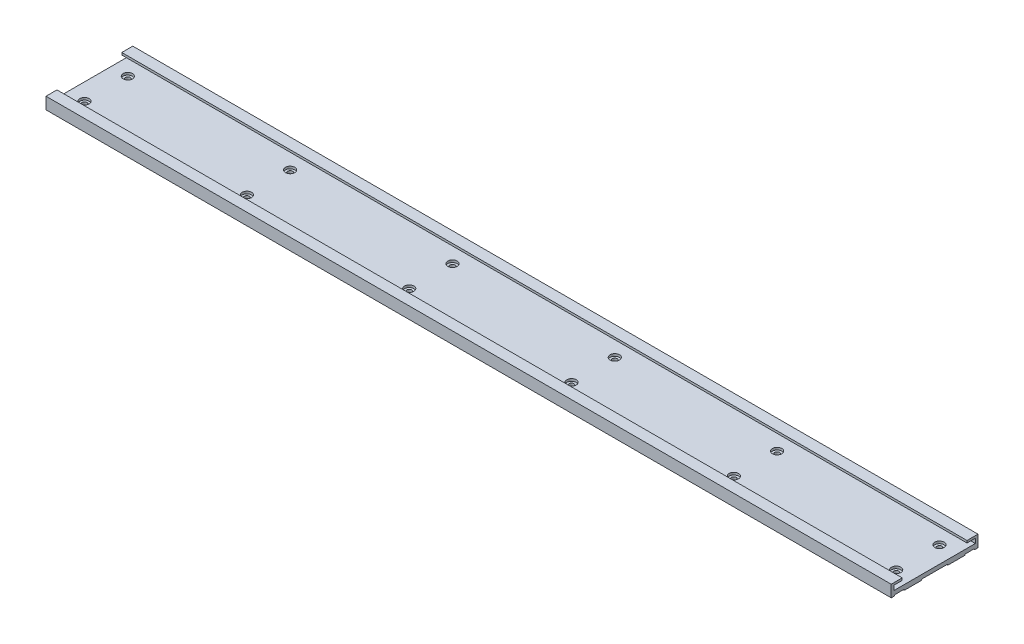
SolidWorks part; units mm, degrees
ref_plane "Front Plane" through (0, 0, 0) normal (0, 0, 1) x (1, 0, 0)
ref_plane "Top Plane" through (0, 0, 0) normal (0, 1, 0) x (1, 0, 0)
ref_plane "Right Plane" through (0, 0, 0) normal (1, 0, 0) x (0, 0, -1)
sketch "Sketch1" plane through (0, 0, 0) normal (0, 1, 0) x (1, 0, 0)
  line L1 (-390.525, -40.0876) -> (390.525, -40.0876)
  line L2 (-390.525, -40.0876) -> (-390.525, 40.0876)
  line L3 (-390.525, 40.0876) -> (390.525, 40.0876)
  line L4 (390.525, -40.0876) -> (390.525, 40.0876)
  point P4 (390.525, 0)
  dimension "D1" = 80.1751
  dimension "D2" = 781.05
extrude "Boss-Extrude1" add sketch "Sketch1" along normal blind 10.922
sketch "Sketch2" plane through (0, 0, 0) normal (0, -1, 0) x (1, 0, 0)
  line L0 (390.525, 40.0876) -> (390.525, -40.0876) construction
  line L1 (-390.525, 40.0876) -> (390.525, 40.0876) construction
  line L2 (-390.525, 40.0876) -> (-390.525, 36.976) construction
  line L3 (-390.525, 36.976) -> (390.525, 36.976)
  line L4 (390.525, 40.0876) -> (390.525, 36.976) construction
  line L5 (390.525, 0) -> (-390.525, 0) construction
  line L6 (-390.525, -40.0876) -> (390.525, -40.0876) construction
  line L7 (-390.525, -40.0876) -> (-390.525, -36.976) construction
  line L8 (-390.525, -36.976) -> (390.525, -36.976)
  line L9 (390.525, -40.0876) -> (390.525, -36.976) construction
  line L10 (-390.525, -40.0876) -> (-390.525, 40.0876) construction
  line L11 (-390.525, 12.211) -> (-390.525, -12.2111)
  line L12 (-390.525, 12.211) -> (390.525, 12.211)
  line L13 (390.525, 12.211) -> (390.525, -12.211)
  line L14 (390.525, -12.211) -> (-390.525, -12.2111)
  line L16 (-390.525, 36.976) -> (390.525, 36.976)
  line L17 (-390.525, 36.976) -> (-390.525, 27.9463)
  line L18 (-390.525, 27.9463) -> (390.525, 27.9463)
  line L19 (390.525, 36.976) -> (390.525, 27.9463)
  line L20 (-390.525, -36.976) -> (390.525, -36.976)
  line L21 (-390.525, -36.976) -> (-390.525, -27.9463)
  line L22 (-390.525, -27.9463) -> (390.525, -27.9463)
  line L23 (390.525, -36.976) -> (390.525, -27.9463)
  line M10 (-390.525, 40.0876) -> (-390.525, -40.0876)
  line M12 (390.525, -40.0876) -> (390.525, 40.0876)
  dimension "D1" = 3.1115
  dimension "D2" = 24.4221
  dimension "D3" = 9.0297
extrude "Cut-Extrude1" cut sketch "Sketch2" against normal blind 0.9144 contours L18 L3 M10 M12 | L14 L12 M12 M10 | L22 L8 M10 M12
fillet "Fillet1" radius 0.762 6 edges at (0, 0.9144, -36.976) (0, 0.9144, -27.9463) (0, 0.9144, -12.2111) (0, 0.9144, 12.211) (0, 0.9144, 27.9463) (0, 0.9144, 36.976)
sketch "Sketch3" plane through (390.525, 0, 0) normal (1, 0, 0) x (0, 0, -1)
  line L0 (-29.9276, 10.922) -> (-29.9276, 8.89)
  line L1 (-40.0876, 10.922) -> (40.0876, 10.922) construction
  line L2 (-29.9276, 8.89) -> (-37.6746, 8.89)
  line L3 (-37.6746, 8.89) -> (-37.6746, 4.6355)
  line L4 (-37.6746, 4.6355) -> (37.6746, 4.6355)
  line L5 (37.6746, 4.6355) -> (37.6746, 8.89)
  line L6 (37.6746, 8.89) -> (29.9276, 8.89)
  line L7 (29.9276, 8.89) -> (29.9275, 10.922)
  line L8 (29.9275, 10.922) -> (-29.9276, 10.922)
  line L10 (-28.7083, 0.9144) -> (-36.2141, 0.9144) construction
  line L11 (-40.0876, 10.922) -> (-40.0876, 0) construction
  line L12 (40.0876, 10.922) -> (40.0876, 0) construction
  dimension "D1" = 3.7211
  dimension "D2" = 2.413
  dimension "D3" = 2.413
  dimension "D4" = 7.747
  dimension "D5" = 2.032
extrude "Cut-Extrude2" cut sketch "Sketch3" against normal through all
ref_plane "Plane1" through (0, 0, 0) normal (0, 0, -1) x (-1, 0, 0)
sketch "Sketch6" plane through (0, 4.6355, 0) normal (0, 1, 0) x (1, 0, 0)
  line L0 (75, -20) -> (75, 0) construction
  line L1 (6.0071, 0) -> (-6.0071, 0) construction
  line L2 (75, 0) -> (75, 20) construction
  line L3 (0, -29.9276) -> (0, 29.9275) construction
  line L4 (-390.525, -29.9276) -> (390.525, -29.9276) construction
  line L5 (-390.525, 29.9275) -> (390.525, 29.9275) construction
  circle A0 centre (75, -20) radius 2.286
  circle A1 centre (75, 20) radius 2.286
  dimension "D2" = 4.572
  dimension "D1" = 75
  dimension "D3" = 40
extrude "Cut-Extrude4" cut sketch "Sketch6" against normal through all
pattern_linear "LPattern1" count 5 spacing 150 along (1, 0, 0) of "Cut-Extrude4"
pattern_linear "LPattern2" count 4 spacing 150 along (-1, 0, 0) of "Cut-Extrude4"
sketch "Sketch7" plane through (0, 4.6355, 0) normal (0, 1, 0) x (1, 0, 0)
  circle A0 centre (375, -20) radius 4.318
  circle A1 centre (375, 20) radius 4.318
  dimension "D1" = 8.636
extrude "Cut-Extrude5" cut sketch "Sketch7" against normal blind 2.159
pattern_linear "LPattern3" count 6 spacing 150 along (-1, 0, 0) of "Cut-Extrude5"
ref_plane "Plane2" through (0, 5.461, 0) normal (0, 1, 0) x (1, 0, 0)
equation "\"D3@Sketch3\"=\"D2@Sketch3\""
